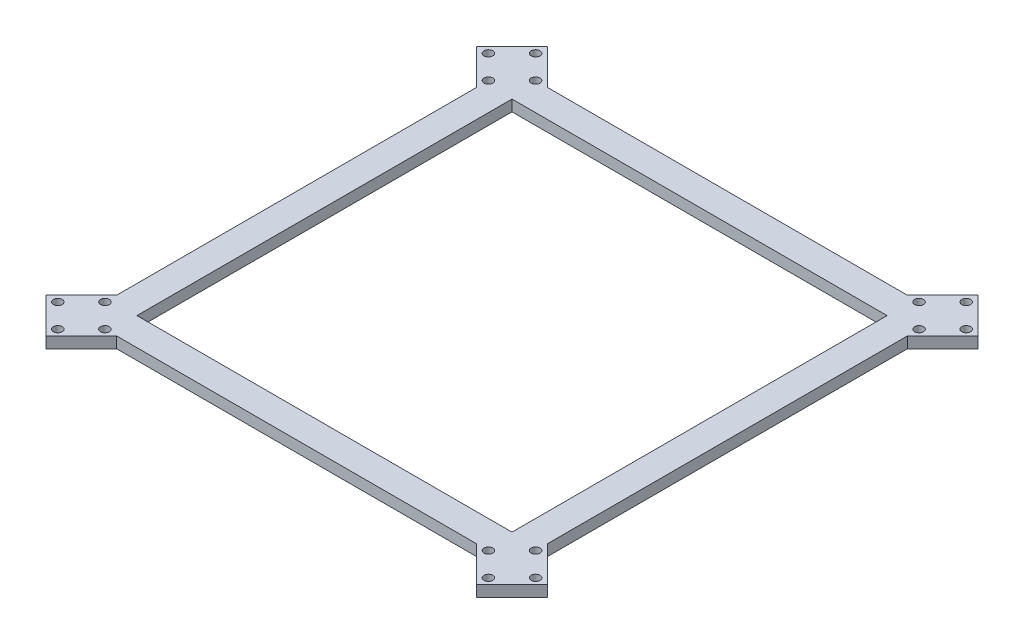
SolidWorks part; units mm, degrees
ref_plane "前视基准面" through (0, 0, 0) normal (0, 0, 1) x (1, 0, 0)
ref_plane "上视基准面" through (0, 0, 0) normal (0, 1, 0) x (1, 0, 0)
ref_plane "右视基准面" through (0, 0, 0) normal (1, 0, 0) x (0, 0, -1)
other "Configuration Table"
sketch "草图1" plane through (0, 0, 0) normal (0, 1, 0) x (1, 0, 0)
  line L0 (-77.5, 0) -> (77.5, 0) construction
  line L1 (-77.5, -77.5) -> (77.5, -77.5) construction
  line L2 (-77.5, -77.5) -> (-77.5, 77.5) construction
  line L3 (-77.5, 77.5) -> (77.5, 77.5) construction
  line L4 (77.5, -77.5) -> (77.5, 77.5) construction
  line L5 (-77.5, -77.5) -> (77.5, 77.5) construction
  line L6 (-77.5, 77.5) -> (77.5, -77.5) construction
  line L7 (77.5, 69.0147) -> (85.9853, 77.5) construction
  line L8 (77.5, 69.0147) -> (69.0147, 77.5) construction
  line L9 (69.0147, 77.5) -> (77.5, 85.9853) construction
  line L10 (85.9853, 77.5) -> (77.5, 85.9853) construction
  line L11 (77.5, 69.0147) -> (77.5, 85.9853) construction
  line L12 (69.0147, 77.5) -> (85.9853, 77.5) construction
  line L13 (90.2279, 77.5) -> (77.5, 64.7721)
  line L14 (90.2279, 77.5) -> (77.5, 90.2279)
  line L15 (77.5, 90.2279) -> (64.7721, 77.5)
  line L16 (77.5, 64.7721) -> (64.7721, 77.5) construction
  line L17 (90.2279, 77.5) -> (64.7721, 77.5) construction
  line L18 (77.5, 90.2279) -> (77.5, 64.7721) construction
  line L19 (0, -77.5) -> (0, 77.5) construction
  line L20 (77.5, 64.7721) -> (77.5, -64.7721)
  line L21 (64.7721, 77.5) -> (-64.7721, 77.5)
  line L22 (77.5, -90.2279) -> (77.5, -64.7721) construction
  line L23 (90.2279, -77.5) -> (64.7721, -77.5) construction
  line L24 (77.5, -64.7721) -> (64.7721, -77.5) construction
  line L25 (69.0147, -77.5) -> (85.9853, -77.5) construction
  line L26 (77.5, -69.0147) -> (77.5, -85.9853) construction
  line L27 (85.9853, -77.5) -> (77.5, -85.9853) construction
  line L28 (69.0147, -77.5) -> (77.5, -85.9853) construction
  line L29 (77.5, -69.0147) -> (69.0147, -77.5) construction
  line L30 (77.5, -69.0147) -> (85.9853, -77.5) construction
  line L31 (64.7721, -77.5) -> (-64.7721, -77.5)
  line L32 (77.5, -90.2279) -> (64.7721, -77.5)
  line L33 (90.2279, -77.5) -> (77.5, -90.2279)
  line L34 (90.2279, -77.5) -> (77.5, -64.7721)
  line L35 (-77.5, -69.0147) -> (-85.9853, -77.5) construction
  line L36 (-77.5, -69.0147) -> (-69.0147, -77.5) construction
  line L37 (-69.0147, -77.5) -> (-77.5, -85.9853) construction
  line L38 (-85.9853, -77.5) -> (-77.5, -85.9853) construction
  line L39 (-77.5, -69.0147) -> (-77.5, -85.9853) construction
  line L40 (-69.0147, -77.5) -> (-85.9853, -77.5) construction
  line L41 (-77.5, -64.7721) -> (-64.7721, -77.5) construction
  line L42 (-90.2279, -77.5) -> (-64.7721, -77.5) construction
  line L43 (-77.5, -90.2279) -> (-77.5, -64.7721) construction
  line L44 (-77.5, 90.2279) -> (-77.5, 64.7721) construction
  line L45 (-90.2279, 77.5) -> (-64.7721, 77.5) construction
  line L46 (-77.5, 64.7721) -> (-64.7721, 77.5) construction
  line L47 (-69.0147, 77.5) -> (-85.9853, 77.5) construction
  line L48 (-77.5, 69.0147) -> (-77.5, 85.9853) construction
  line L49 (-85.9853, 77.5) -> (-77.5, 85.9853) construction
  line L50 (-69.0147, 77.5) -> (-77.5, 85.9853) construction
  line L51 (-77.5, 69.0147) -> (-69.0147, 77.5) construction
  line L52 (-77.5, 69.0147) -> (-85.9853, 77.5) construction
  line L53 (-77.5, -77.5) -> (-77.5, 77.5) construction
  line L54 (-90.2279, -77.5) -> (-77.5, -64.7721)
  line L55 (-90.2279, -77.5) -> (-77.5, -90.2279)
  line L56 (-77.5, -90.2279) -> (-64.7721, -77.5)
  line L57 (-77.5, 64.7721) -> (-77.5, -64.7721)
  line L58 (-77.5, 90.2279) -> (-64.7721, 77.5)
  line L59 (-90.2279, 77.5) -> (-77.5, 90.2279)
  line L60 (-90.2279, 77.5) -> (-77.5, 64.7721)
  line L62 (-67.5, -67.5) -> (67.5, -67.5)
  line L63 (-67.5, -67.5) -> (-67.5, 67.5)
  line L64 (-67.5, 67.5) -> (67.5, 67.5)
  line L65 (67.5, -67.5) -> (67.5, 67.5)
  line L66 (-67.5, -67.5) -> (67.5, 67.5) construction
  line L67 (-67.5, 67.5) -> (67.5, -67.5) construction
  circle A0 centre (77.5, 85.9853) radius 1.6
  circle A1 centre (69.0147, 77.5) radius 1.6
  circle A2 centre (77.5, 69.0147) radius 1.6
  circle A3 centre (85.9853, 77.5) radius 1.6
  circle A4 centre (85.9853, -77.5) radius 1.6
  circle A5 centre (77.5, -69.0147) radius 1.6
  circle A6 centre (69.0147, -77.5) radius 1.6
  circle A7 centre (77.5, -85.9853) radius 1.6
  circle A8 centre (-77.5, -85.9853) radius 1.6
  circle A9 centre (-69.0147, -77.5) radius 1.6
  circle A10 centre (-77.5, -69.0147) radius 1.6
  circle A11 centre (-85.9853, -77.5) radius 1.6
  circle A12 centre (-85.9853, 77.5) radius 1.6
  circle A13 centre (-77.5, 69.0147) radius 1.6
  circle A14 centre (-69.0147, 77.5) radius 1.6
  circle A15 centre (-77.5, 85.9853) radius 1.6
  point P0 (0, 0)
  point P51 (0, 0)
  point P59 (0, 0)
  dimension "D4" = 3.2
  dimension "D1" = 155
  dimension "D2" = 12
  dimension "D3" = 12
  dimension "D5" = 18
  dimension "D6" = 135
extrude "凸台-拉伸1" add sketch "草图1" along normal blind 4
